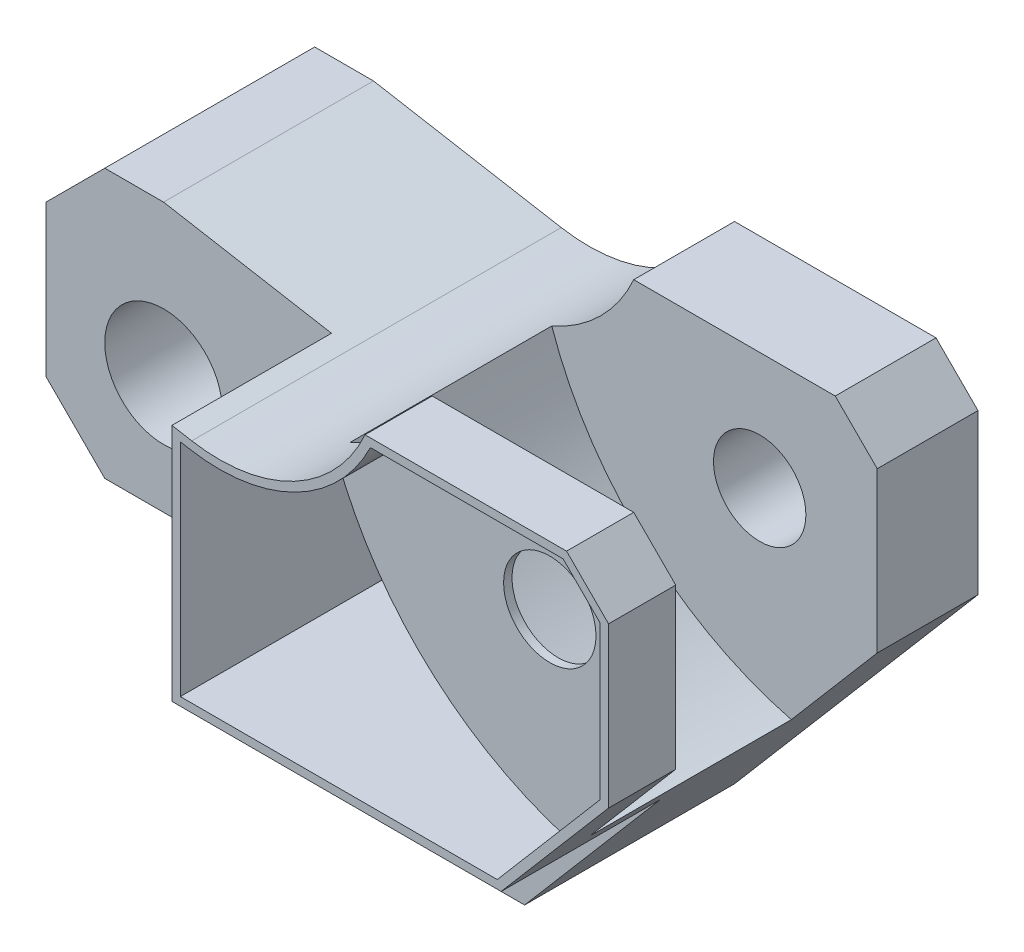
SolidWorks part; units mm, degrees
material "AISI 1020"
ref_plane "Front Plane" through (0, 0, 0) normal (0, 0, 1) x (1, 0, 0)
ref_plane "Top Plane" through (0, 0, 0) normal (0, 1, 0) x (1, 0, 0)
ref_plane "Right Plane" through (0, 0, 0) normal (1, 0, 0) x (0, 0, -1)
sketch "Sketch1" plane through (0, 0, 0) normal (0, 0, 1) x (1, 0, 0)
  line L0 (0, 7) -> (0, 25)
  line L1 (7, 32) -> (14, 32)
  line L2 (14, 32) -> (36.3614, 28.0571)
  line L3 (57, 39) -> (81, 39)
  line L4 (86, 34) -> (86, 15)
  line L5 (86, 15) -> (57, -19)
  line L6 (57, -19) -> (51.297, -19)
  line L7 (39.5755, 0) -> (7, 0)
  line L8 (0, 25) -> (7, 32)
  line L9 (7, 0) -> (0, 7)
  line L10 (81, 39) -> (86, 34)
  arc A0 (36.3614, 28.0571) -> (57, 39) centre (39.6607, 46.7684) ccw
  arc A1 (39.5755, 0) -> (44.5212, -4.2647) centre (39.5755, -5) cw
  arc A2 (44.5212, -4.2647) -> (51.297, -19) centre (73.2059, 0) ccw
  circle A3 centre (14, 14) radius 7
  point P0 (0, 0)
  point P1 (0, 32)
  point P9 (86, 39)
  dimension "D8" = 19
  dimension "D15" = 5
  dimension "D16" = 29
  dimension "D19" = 14
  dimension "D1" = 86
  dimension "D2" = 58
  dimension "D3" = 32
  dimension "D4" = 14
  dimension "D5" = 10
  dimension "D9" = 29
  dimension "D10" = 24
  dimension "D11" = 29
  dimension "D12" = 19
  dimension "D14" = 19
  dimension "D17" = 14
  dimension "D18" = 14
extrude "Boss-Extrude1" add sketch "Sketch1" along normal blind 44
ref_plane "Plane1" through (0, 0, 12) normal (0, 0, -1) x (-1, 0, 0)
sketch "Sketch3" plane through (0, 0, 12) normal (0, 0, -1) x (-1, 0, 0)
  line L0 (-86, 15) -> (-86, 34) construction
  line L1 (-57, -19) -> (-86, 15) construction
  line L13 (-14, 32) -> (-36.3614, 28.0571)
  line L14 (-7, 32) -> (-14, 32)
  line L15 (0, 25) -> (-7, 32)
  line L16 (0, 7) -> (0, 25)
  line L17 (-7, 0) -> (0, 7)
  line L18 (-39.5755, 0) -> (-7, 0)
  line L19 (-57, -19) -> (-51.297, -19)
  line L20 (-86, 15) -> (-57, -19)
  line L21 (-86, 34) -> (-86, 15)
  line L22 (-81, 39) -> (-86, 34)
  line L23 (-57, 39) -> (-81, 39)
  line L24 (-14, 32) -> (-36.3614, 28.0571)
  line L25 (-7, 32) -> (-14, 32)
  line L26 (0, 25) -> (-7, 32)
  line L27 (0, 7) -> (0, 25)
  line L28 (-7, 0) -> (0, 7)
  line L29 (-39.5755, 0) -> (-7, 0)
  line L30 (-57, -19) -> (-51.297, -19)
  line L31 (-86, 15) -> (-57, -19)
  line L32 (-86, 34) -> (-86, 15)
  line L33 (-81, 39) -> (-86, 34)
  line L34 (-57, 39) -> (-81, 39)
  circle A0 centre (-86, 42.7019) radius 41
  arc A4 (-39.5755, 0) -> (-44.5212, -4.2647) centre (-39.5755, -5) ccw
  arc A5 (-51.297, -19) -> (-44.5212, -4.2647) centre (-73.2059, 0) ccw
  arc A6 (-57, 39) -> (-36.3614, 28.0571) centre (-39.6607, 46.7684) ccw
  arc A7 (-39.5755, 0) -> (-44.5212, -4.2647) centre (-39.5755, -5) ccw
  arc A8 (-51.297, -19) -> (-44.5212, -4.2647) centre (-73.2059, 0) ccw
  arc A9 (-57, 39) -> (-36.3614, 28.0571) centre (-39.6607, 46.7684) ccw
  point P2 (-75.7647, 3)
  point P3 (-84.2788, 12.9821)
  point P6 (0, 0)
  point P7 (0, 0)
  point P8 (-86, 44)
  dimension "D1" = 82
  dimension "D3" = 36
  dimension "D2" = 0
extrude "Cut-Extrude1" cut sketch "Sketch3" against normal blind 24 contours A0
sketch "Sketch4" plane through (86, 0, 0) normal (1, 0, 0) x (0, 0, -1)
  line L0 (-44, -19) -> (0, -19) construction
  line L1 (-44, -19) -> (-44, 15) construction
  line L2 (-44, -19) -> (0, -19)
  line L3 (-44, -19) -> (-44, 15)
  line L5 (-44, -19) -> (-25, -19)
  line L6 (-44, -19) -> (-44, 0)
  line L7 (-44, 0) -> (-25, 0)
  line L8 (-25, -19) -> (-25, 0)
  dimension "D1" = 19
extrude "Cut-Extrude2" cut sketch "Sketch4" against normal through all contours L2 L8 L7 L3
sketch "Sketch5" plane through (0, 0, 44) normal (0, 0, 1) x (1, 0, 0)
  line L0 (86, 15) -> (86, 34) construction
  line L1 (0, 0) -> (34, 0)
  line L2 (0, 0) -> (0, 32)
  line L3 (0, 32) -> (34, 32)
  line L4 (34, 0) -> (34, 32)
  line L5 (14, 32) -> (7, 32) construction
  line L6 (7, 0) -> (73.2059, 0) construction
  line L7 (0, 25) -> (0, 7) construction
  dimension "D1" = 52
extrude "Cut-Extrude4" cut sketch "Sketch5" against normal blind 19
sketch "Sketch6" plane through (0, 0, 44) normal (0, 0, 1) x (1, 0, 0)
  line L2 (86, 15) -> (86, 34) construction
  line L4 (81, 39) -> (57, 39) construction
  circle A0 centre (72, 25) radius 5.5
  point P6 (53.2316, 24.5917)
  point P9 (0, 0)
  dimension "D1" = 11
  dimension "D2" = 14
  dimension "D3" = 14
extrude "Cut-Extrude5" cut sketch "Sketch6" against normal through all
sketch "Sketch8" plane through (0, 0, 44) normal (0, 0, 1) x (1, 0, 0)
  line L14 (35, 27.2817) -> (35, 1)
  line L15 (35, 1) -> (72.7445, 1)
  line L16 (72.7445, 1) -> (85, 15.3685)
  line L17 (85, 15.3685) -> (85, 33.5858)
  line L18 (85, 33.5858) -> (80.5858, 38)
  line L19 (80.5858, 38) -> (57.6361, 38)
  line L20 (36.1877, 27.0723) -> (35, 27.2817)
  line L21 (35, 27.2817) -> (35, 1)
  line L22 (35, 1) -> (72.7445, 1)
  line L23 (72.7445, 1) -> (85, 15.3685)
  line L24 (85, 15.3685) -> (85, 33.5858)
  line L25 (85, 33.5858) -> (80.5858, 38)
  line L26 (80.5858, 38) -> (57.6361, 38)
  line L27 (36.1877, 27.0723) -> (35, 27.2817)
  arc A2 (36.1877, 27.0723) -> (57.6361, 38) centre (39.6607, 46.7684) ccw
  arc A3 (36.1877, 27.0723) -> (57.6361, 38) centre (39.6607, 46.7684) ccw
  dimension "D1" = 1
extrude "Cut-Extrude6" cut sketch "Sketch8" against normal offset from surface (7 mm away) 1 contours L21 L22 L23 L24 L25 L26 A3 L27 up to face at (66.5, 25, 36)
sketch "Sketch9" plane through (0, 0, 37) normal (0, 0, 1) x (1, 0, 0)
  line L7 (36.1877, 27.0723) -> (35, 27.2817)
  line L8 (35, 27.2817) -> (35, 1)
  line L9 (35, 1) -> (72.7445, 1)
  line L10 (72.7445, 1) -> (85, 15.3685)
  line L11 (85, 15.3685) -> (85, 33.5858)
  line L12 (85, 33.5858) -> (80.5858, 38)
  line L13 (80.5858, 38) -> (57.6361, 38)
  line L14 (36.1877, 27.0723) -> (35, 27.2817)
  line L15 (35, 27.2817) -> (35, 1)
  line L16 (35, 1) -> (72.7445, 1)
  line L17 (72.7445, 1) -> (85, 15.3685)
  line L18 (85, 15.3685) -> (85, 33.5858)
  line L19 (85, 33.5858) -> (80.5858, 38)
  line L20 (80.5858, 38) -> (57.6361, 38)
  arc A1 (47.2369, 29.3443) -> (75.7647, 3) centre (86, 42.7019) ccw construction
  arc A2 (47.2369, 29.3443) -> (75.7647, 3) centre (86, 42.7019) ccw
  arc A3 (46.2915, 29.0185) -> (75.5151, 2.0317) centre (86, 42.7019) ccw
  arc A5 (36.1877, 27.0723) -> (57.6361, 38) centre (39.6607, 46.7684) ccw
  arc A6 (36.1877, 27.0723) -> (57.6361, 38) centre (39.6607, 46.7684) ccw
  line M9 (36.1877, 27.0723) -> (35, 27.2817)
  line M10 (35, 27.2817) -> (35, 1)
  line M11 (35, 1) -> (72.7445, 1)
  line M12 (72.7445, 1) -> (85, 15.3685)
  arc M16 (57.6361, 38) -> (36.1877, 27.0723) centre (39.6607, 46.7684) cw
  dimension "D1" = 1
  dimension "D2" = 0
extrude "Cut-Extrude11" cut sketch "Sketch9" against normal offset from surface (25 mm away) 12 contours A3 M16 M9 M10 M11 M12 up to face at (77.5, 25, 0)
equation "\"A\" = 86"
equation "\"B\" = 58"
equation "\"C\"= 44"
equation "\"D1@Sketch1\"=\"A\""
equation "\"D2@Sketch1\"=\"B\""
equation "\"D1@Boss-Extrude1\"=\"C\""
